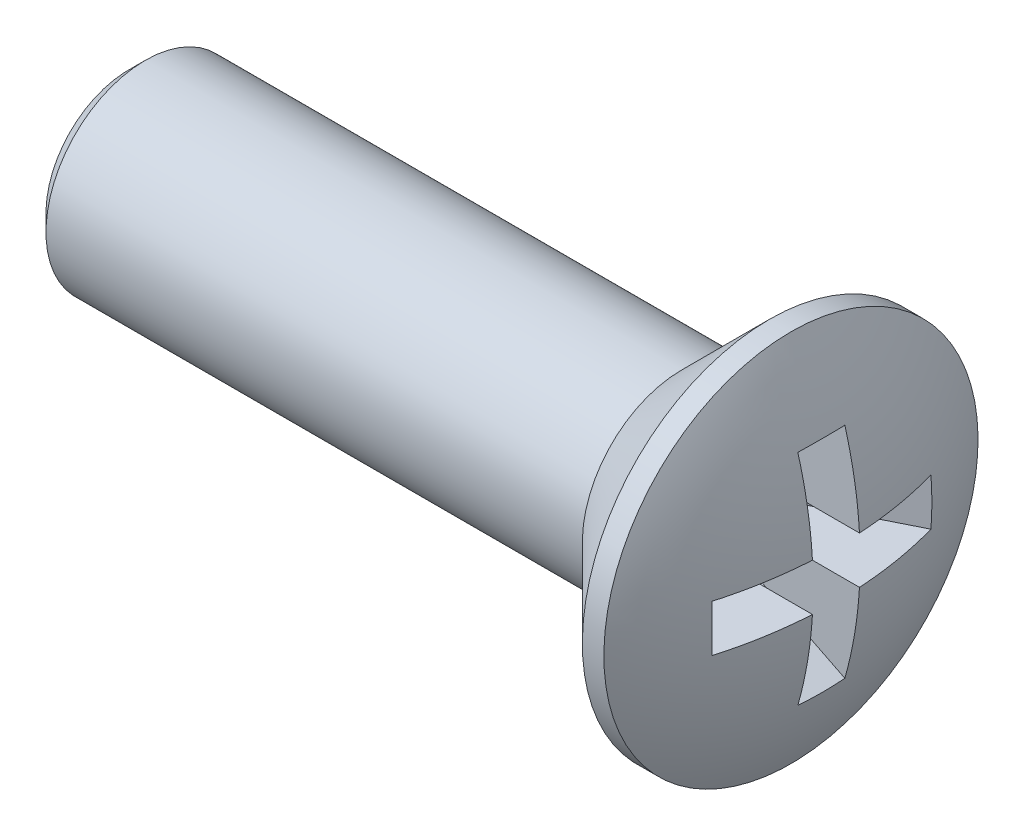
SolidWorks part; units mm, degrees
material "AISI 1020"
ref_plane "Front Plane" through (0, 0, 0) normal (0, 0, 1) x (1, 0, 0)
ref_plane "Top Plane" through (0, 0, 0) normal (0, 1, 0) x (1, 0, 0)
ref_plane "Right Plane" through (0, 0, 0) normal (1, 0, 0) x (0, 0, -1)
sketch "Sketch1" plane through (0, 0, 0) normal (0, 0, 1) x (1, 0, 0)
  line L0 (0, 0) -> (-21.4, 0) construction
  line L1 (-1.4, 5.65) -> (-2.05, 5.65)
  line L2 (-2.05, 5.65) -> (-4.7, 3)
  line L3 (-4.7, 3) -> (-21.4, 3)
  line L4 (-21.4, 3) -> (-21.4, 0)
  line L5 (-21.4, 0) -> (0, 0)
  arc A0 (0, 0) -> (-1.4, 5.65) centre (-12.1009, 0) ccw
  dimension "Diam" = 6
  dimension "G_diam" = 11.3
  dimension "G_s_plotis" = 1.4
  dimension "G_plotis" = 3.3
  dimension "D5" = 45
  dimension "Ilgis" = 20
revolve "Revolve1" add sketch "Sketch1" angle 360 about L0
cosmetic thread "Cosmetic Thread1" parameters "Sr_ilgis"=16.7, "Sr_diam"=5
sketch "Sketch2" plane through (0, 0, 0) normal (1, 0, 0) x (0, 0, -1)
  line L0 (-3.55, -0.71) -> (3.55, 0.71) construction
  line L1 (-3.55, 0.71) -> (3.55, 0.71)
  line L2 (-3.55, 0.71) -> (-3.55, -0.71)
  line L3 (-3.55, -0.71) -> (3.55, -0.71)
  line L4 (3.55, 0.71) -> (3.55, -0.71)
  line L5 (-0.71, -3.55) -> (0.71, -3.55)
  line L6 (-0.71, -3.55) -> (-0.71, 3.55)
  line L7 (-0.71, 3.55) -> (0.71, 3.55)
  line L8 (0.71, -3.55) -> (0.71, 3.55)
  line L9 (0.71, 3.55) -> (-0.71, -3.55) construction
  dimension "Y_diam" = 7.1
  dimension "Y_plotis" = 1.42
extrude "Cut-Extrude1" cut sketch "Sketch2" against normal blind 3.85 contours L1 L8 L7 L6 | L3 L6 L1 L2 | L3 L8 L1 L6 | L8 L3 L4 L1 | L5 L8 L3 L6
draft "Draft1" type of draft neutral plane draft angle 26.5 neutral plane "Right Plane" faces to draft 4 face at (-2.1967, -3.55, 0) face at (-2.1967, 0, 3.55) face at (-2.1967, 0, -3.55) face at (-2.1967, 3.55, 0) neutral plane through (0, 0, 0) neutral plane normal (1, 0, 0) parameters "D1"=26.5
chamfer "Chamfer1" distance 0.5 angle 45 1 edges at (-21.4, 3, 0)
